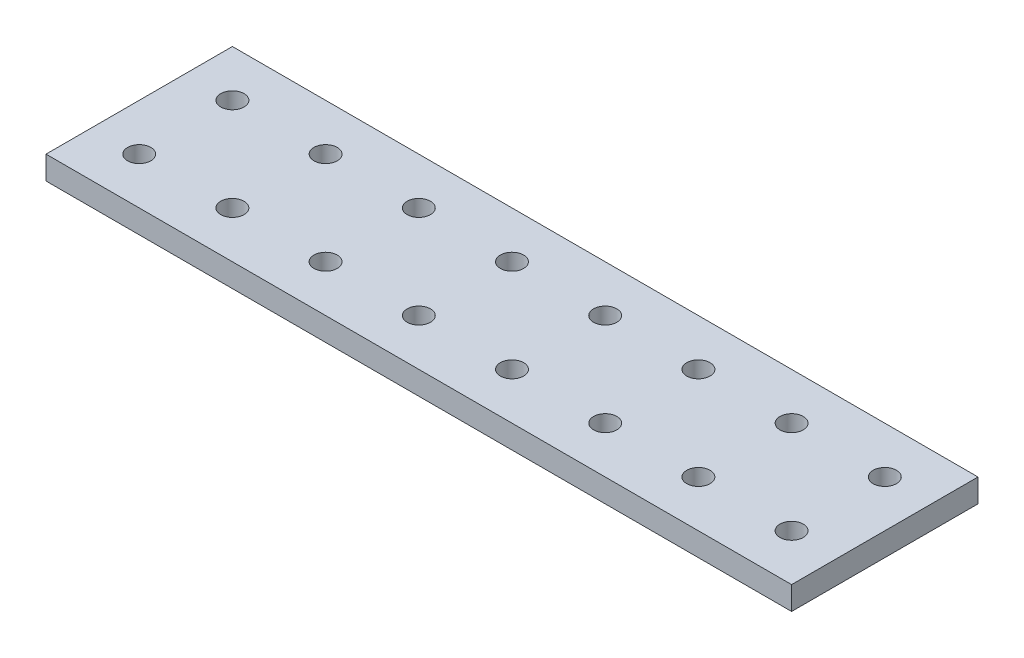
SolidWorks part; units mm, degrees
ref_plane "Front Plane" through (0, 0, 0) normal (0, 0, 1) x (1, 0, 0)
ref_plane "Top Plane" through (0, 0, 0) normal (0, 1, 0) x (1, 0, 0)
ref_plane "Right Plane" through (0, 0, 0) normal (1, 0, 0) x (0, 0, -1)
sketch "Sketch1" plane through (0, 0, 0) normal (0, 1, 0) x (1, 0, 0)
  line L1 (-101.6, -25.4) -> (101.6, -25.4)
  line L2 (-101.6, -25.4) -> (-101.6, 25.4)
  line L3 (-101.6, 25.4) -> (101.6, 25.4)
  line L4 (101.6, -25.4) -> (101.6, 25.4)
  line L5 (-101.6, -25.4) -> (101.6, 25.4) construction
  line L6 (-101.6, 25.4) -> (101.6, -25.4) construction
  circle A0 centre (-88.9, 12.7) radius 3.175
  circle A1 centre (-63.5, 12.7) radius 3.175
  circle A2 centre (-38.1, 12.7) radius 3.175
  circle A3 centre (-12.7, 12.7) radius 3.175
  circle A4 centre (12.7, 12.7) radius 3.175
  circle A5 centre (38.1, 12.7) radius 3.175
  circle A6 centre (63.5, 12.7) radius 3.175
  circle A7 centre (88.9, 12.7) radius 3.175
  circle A8 centre (-63.5, -12.7) radius 3.175
  circle A9 centre (-38.1, -12.7) radius 3.175
  circle A10 centre (-12.7, -12.7) radius 3.175
  circle A11 centre (12.7, -12.7) radius 3.175
  circle A12 centre (38.1, -12.7) radius 3.175
  circle A13 centre (63.5, -12.7) radius 3.175
  circle A14 centre (88.9, -12.7) radius 3.175
  circle A15 centre (-88.9, -12.7) radius 3.175
  point P0 (0, 0)
  dimension "D3" = 6.35
  dimension "D1" = 203.2
  dimension "D2" = 50.8
  dimension "D4" = 12.7
  dimension "D5" = 12.7
  dimension "D6" = 8
  dimension "D7" = 2
extrude "Boss-Extrude1" add sketch "Sketch1" along normal blind 6.35
